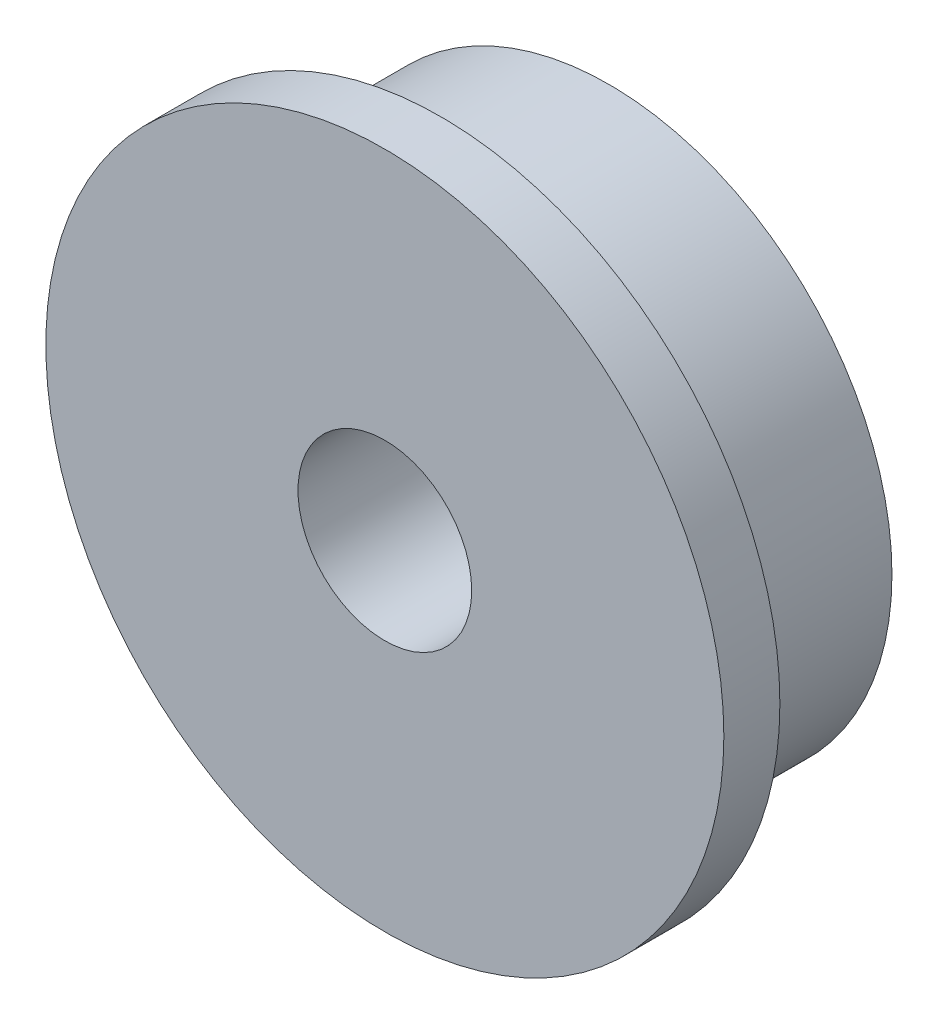
SolidWorks part; units mm, degrees
material "Нержавеющая сталь (ферритная)"
ref_plane "Front Plane" through (0, 0, 0) normal (0, 0, 1) x (1, 0, 0)
ref_plane "Top Plane" through (0, 0, 0) normal (0, 1, 0) x (1, 0, 0)
ref_plane "Right Plane" through (0, 0, 0) normal (1, 0, 0) x (0, 0, -1)
sketch "Sketch1" plane through (0, 0, 0) normal (0, 0, 1) x (1, 0, 0)
  circle A0 centre (0, 0) radius 5.05
  circle A1 centre (0, 0) radius 1.55
  dimension "D1" = 10.1
  dimension "D2" = 3.1
extrude "Boss-Extrude1" add sketch "Sketch1" along normal blind 3
sketch "Sketch2" plane through (0, 0, 3) normal (0, 0, 1) x (1, 0, 0)
  circle A0 centre (0, 0) radius 1.55
  circle A1 centre (0, 0) radius 6.05
  dimension "D1" = 12.1
extrude "Boss-Extrude2" add sketch "Sketch2" along normal blind 1
